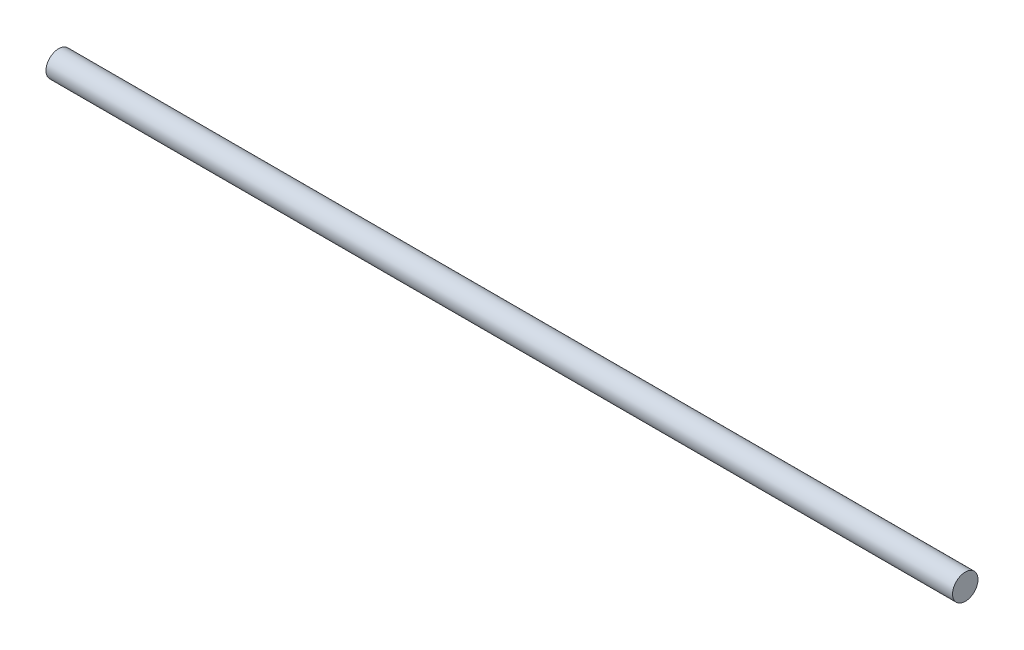
SolidWorks part; units mm, degrees
ref_plane "前视基准面" through (0, 0, 0) normal (0, 0, 1) x (1, 0, 0)
ref_plane "上视基准面" through (0, 0, 0) normal (0, 1, 0) x (1, 0, 0)
ref_plane "右视基准面" through (0, 0, 0) normal (1, 0, 0) x (0, 0, -1)
sketch "草图1" plane through (0, 0, 0) normal (1, 0, 0) x (0, 0, -1)
  circle A0 centre (0, 0) radius 4
  dimension "D1" = 8
extrude "凸台-拉伸1" add sketch "草图1" along normal blind 285
